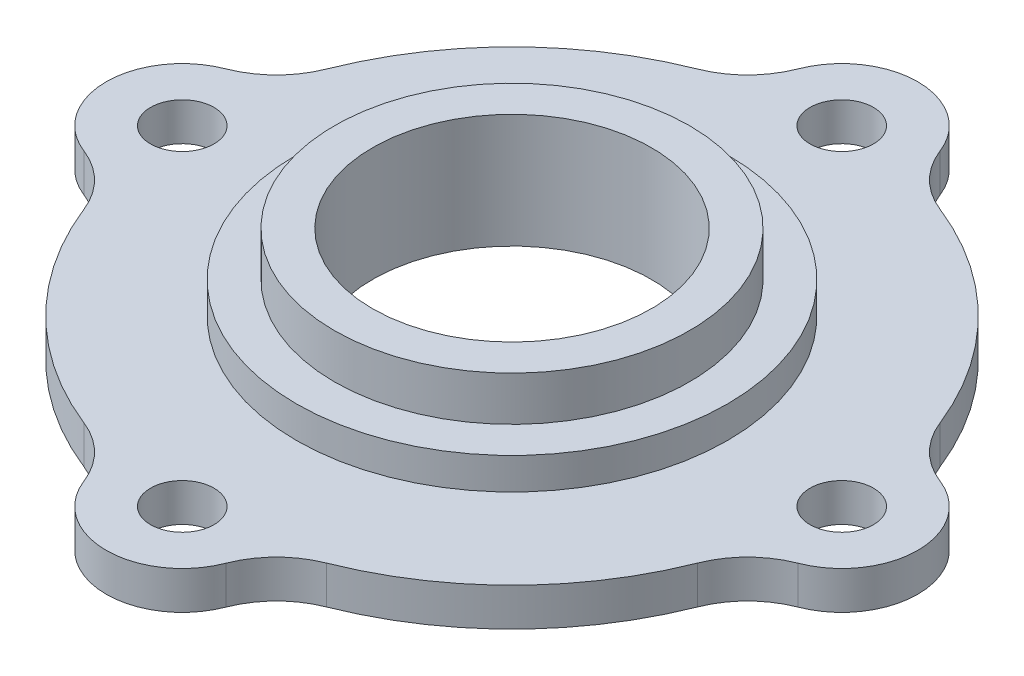
SolidWorks part; units mm, degrees
ref_plane "Front Plane" through (0, 0, 0) normal (0, 0, 1) x (1, 0, 0)
ref_plane "Top Plane" through (0, 0, 0) normal (0, 1, 0) x (1, 0, 0)
ref_plane "Right Plane" through (0, 0, 0) normal (1, 0, 0) x (0, 0, -1)
sketch "Sketch1" plane through (0, 0, 0) normal (0, 1, 0) x (1, 0, 0)
  circle A0 centre (0, 0) radius 431.8
  circle A1 centre (0, 0) radius 355.6
  circle A2 centre (0, 0) radius 279.4
  dimension "D1" = 863.6
  dimension "D2" = 711.2
  dimension "D3" = 558.8
extrude "Boss-Extrude2" add sketch "Sketch1" along normal blind 228.6 contours A1 A2
sketch "Sketch2" plane through (0, 0, 0) normal (0, 1, 0) x (1, 0, 0)
  circle A0 centre (0, 0) radius 431.8
  dimension "D1" = 863.6
extrude "Boss-Extrude3" add sketch "Sketch2" along normal blind 139.7
sketch "Sketch3" plane through (0, 0, 0) normal (0, 1, 0) x (1, 0, 0)
  circle A3 centre (0, 660.4) radius 63.5
  circle A5 centre (660.4, 0) radius 63.5
  arc A6 (-142.1262, -715.4083) -> (142.1262, -715.4083) centre (0, -660.4) ccw
  circle A7 centre (0, -660.4) radius 63.5
  arc A8 (-715.4083, 142.1262) -> (-715.4083, -142.1262) centre (-660.4, 0) ccw
  circle A9 centre (-660.4, 0) radius 63.5
  arc A10 (-715.4083, 142.1262) -> (-614.2182, 242.6194) centre (-779.5846, 307.94) ccw
  arc A11 (-614.2182, -242.6194) -> (-715.4083, -142.1262) centre (-779.5846, -307.94) ccw
  arc A12 (142.1262, 715.4083) -> (242.6194, 614.2182) centre (307.94, 779.5846) ccw
  arc A13 (-242.6194, 614.2182) -> (-142.1262, 715.4083) centre (-307.94, 779.5846) ccw
  arc A14 (715.4083, -142.1262) -> (614.2182, -242.6194) centre (779.5846, -307.94) ccw
  arc A15 (614.2182, 242.6194) -> (715.4083, 142.1262) centre (779.5846, 307.94) ccw
  arc A16 (-142.1262, -715.4083) -> (-242.6194, -614.2182) centre (-307.94, -779.5846) ccw
  arc A17 (242.6194, -614.2182) -> (142.1262, -715.4083) centre (307.94, -779.5846) ccw
  arc A18 (-614.2182, -242.6194) -> (-242.6194, -614.2182) centre (0, 0) ccw
  arc A19 (614.2182, 242.6194) -> (242.6194, 614.2182) centre (0, 0) ccw
  arc A20 (242.6194, -614.2182) -> (614.2182, -242.6194) centre (0, 0) ccw
  arc A21 (715.4083, -142.1262) -> (715.4083, 142.1262) centre (660.4, 0) ccw
  arc A22 (-242.6194, 614.2182) -> (-614.2182, 242.6194) centre (0, 0) ccw
  arc A25 (142.1262, 715.4083) -> (-142.1262, 715.4083) centre (0, 660.4) ccw
  point P6 (0, 571.5)
  point P20 (0, 0)
  point P45 (0, 0)
  dimension "D3" = 127
  dimension "D6" = 355.6
  dimension "D7" = 355.6
  dimension "D4" = 4
  dimension "D8" = 4
extrude "Boss-Extrude4" add sketch "Sketch3" along normal blind 76.2
sketch "Sketch4" plane through (0, 139.7, 0) normal (0, 1, 0) x (1, 0, 0)
  circle A0 centre (0, 0) radius 279.4
extrude "Cut-Extrude1" cut sketch "Sketch4" against normal up to next
